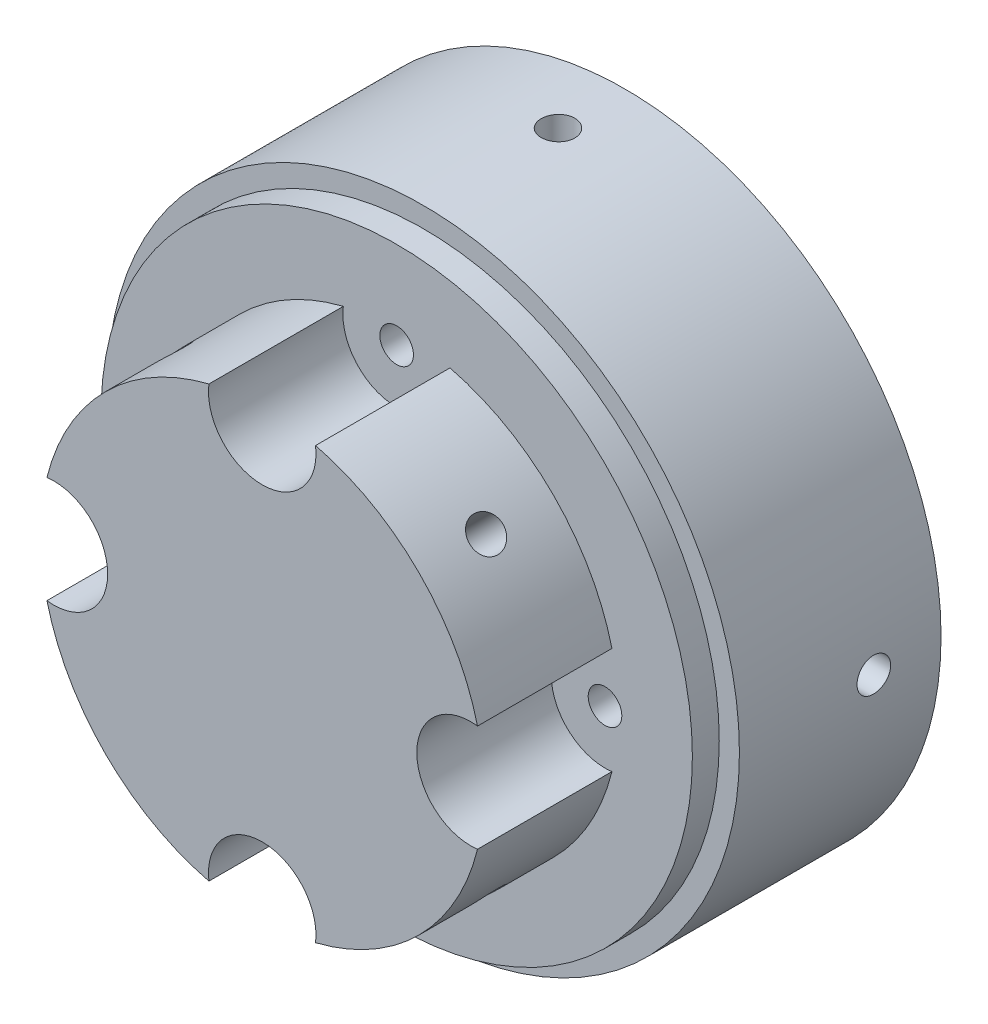
SolidWorks part; units mm, degrees
ref_plane "前视基准面" through (0, 0, 0) normal (0, 0, 1) x (1, 0, 0)
ref_plane "上视基准面" through (0, 0, 0) normal (0, 1, 0) x (1, 0, 0)
ref_plane "右视基准面" through (0, 0, 0) normal (1, 0, 0) x (0, 0, -1)
sketch "草图1" plane through (0, 0, 0) normal (0, 0, 1) x (1, 0, 0)
  circle A0 centre (0, 0) radius 23.5
  circle A1 centre (0, 0) radius 21
  dimension "D1" = 47
  dimension "D2" = 42
extrude "凸台-拉伸1" add sketch "草图1" along normal blind 15
sketch "草图2" plane through (0, 0, 0) normal (1, 0, 0) x (0, 0, -1)
  line L0 (0, -23.5) -> (0, 23.5) construction
  line L1 (-15, 23.5) -> (-15, -23.5) construction
  line L2 (0, -23.5) -> (0, 23.5)
  line L3 (-15, 23.5) -> (-15, -23.5)
  line L6 (-15, 0) -> (-5, 0)
  circle A0 centre (-5, 0) radius 1.25
  dimension "D2" = 2.5
  dimension "D1" = 10
extrude "切除-拉伸1" cut sketch "草图2" against normal mid plane 54 contours A0
pattern_circular "阵列(圆周)1" count 4 over 360 about axis through (0, 0, 15) along (0, 0, -1) of "切除-拉伸1"
sketch "草图3" plane through (0, 0, 15) normal (0, 0, 1) x (1, 0, 0)
  circle A0 centre (0, 0) radius 22
  dimension "D1" = 44
extrude "凸台-拉伸2" add sketch "草图3" along normal blind 2
sketch "草图4" plane through (0, 0, 17) normal (0, 0, 1) x (1, 0, 0)
  line L0 (0, 0) -> (21, 0)
  line L1 (21, 0) -> (15.5, 0)
  circle A0 centre (0, 0) radius 21 construction
  circle A1 centre (0, 0) radius 21
  circle A2 centre (15.5, 0) radius 1.25
  circle A3 centre (0, -15.5) radius 1.25
  circle A4 centre (-15.5, 0) radius 1.25
  circle A5 centre (0, 15.5) radius 1.25
  point P15 (0, 0)
  dimension "D1" = 5.5
  dimension "D2" = 2.5
  dimension "D3" = 4
extrude "切除-拉伸2" cut sketch "草图4" against normal up to surface (2 mm away) contours A3 | A2 | A5 | A4 up to face at (21, 0, 15)
sketch "草图5" plane through (0, 0, 17) normal (0, 0, 1) x (1, 0, 0)
  circle A0 centre (0, 0) radius 16.5
  dimension "D1" = 33
extrude "凸台-拉伸4" add sketch "草图5" along normal blind 10
sketch "草图6" plane through (0, 0, 27) normal (0, 0, 1) x (1, 0, 0)
  circle A0 centre (-15.5, 0) radius 1.25 construction
  circle A1 centre (0, -15.5) radius 1.25 construction
  circle A2 centre (15.5, 0) radius 1.25 construction
  circle A3 centre (0, 15.5) radius 1.25 construction
  circle A4 centre (-15.5, 0) radius 1.25
  circle A5 centre (0, -15.5) radius 1.25
  circle A6 centre (15.5, 0) radius 1.25
  circle A7 centre (0, 15.5) radius 1.25
  circle A8 centre (0, -15.5) radius 4
  circle A9 centre (-15.5, 0) radius 4
  circle A10 centre (0, 15.5) radius 4
  circle A11 centre (15.5, 0) radius 4
  point P22 (0, 0)
  circle M6 centre (0, 0) radius 16.5
  dimension "D1" = 8
  dimension "D2" = 4
extrude "切除-拉伸5" cut sketch "草图6" against normal up to surface (10 mm away) contours A11 A6 M6 | A10 A7 M6 | A8 A5 M6 | A9 A4 M6 | A5 M6 | A6 M6 | A4 M6
sketch "草图7" plane through (0, 0, 27) normal (0, 0, 1) x (1, 0, 0)
  line L0 (11.6673, 11.6673) -> (-11.6673, -11.6673)
  arc A0 (16.0161, 3.9666) -> (3.9666, 16.0161) centre (0, 0) ccw construction
  arc A1 (-16.0161, -3.9666) -> (-3.9666, -16.0161) centre (0, 0) ccw construction
ref_plane "基准面5" through (11.6673, 11.6673, 0) normal (0.7071, 0.7071, 0) x (0, 0, -1)
sketch "草图8" plane through (11.6673, 11.6673, 0) normal (0.7071, 0.7071, 0) x (0, 0, -1)
  line L0 (-27, 0) -> (-17, 0)
  line L1 (-17, 0) -> (-22, 0)
  line L4 (-27, 8.5203) -> (-27, -8.5203)
  line L5 (-27, -8.5203) -> (-17, -8.5203)
  line L6 (-17, -8.5203) -> (-17, 8.5203)
  line L7 (-17, 8.5203) -> (-27, 8.5203)
  line L8 (-27, 8.5203) -> (-27, -8.5203)
  line L9 (-27, -8.5203) -> (-17, -8.5203)
  line L10 (-17, -8.5203) -> (-17, 8.5203)
  line L11 (-17, 8.5203) -> (-27, 8.5203)
  circle A0 centre (-22, 0) radius 1.25
  dimension "D3" = 2.5
  dimension "D2" = 5
  dimension "D1" = 0
extrude "切除-拉伸6" cut sketch "草图8" against normal blind 43 contours A0
pattern_circular "阵列(圆周)2" count 4 over 360 about axis through (0, 0, 27) along (0, 0, 1) of "切除-拉伸6"
